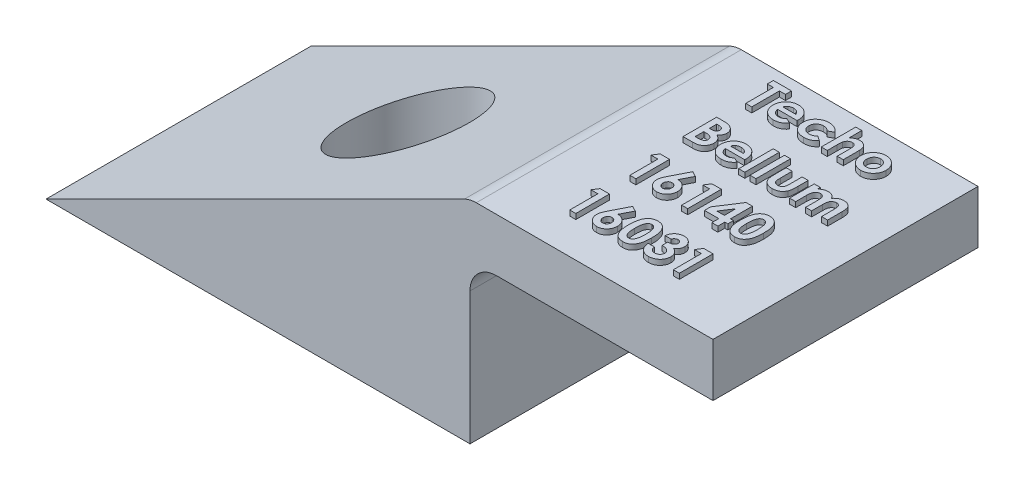
SolidWorks part; units mm, degrees
ref_plane "Front" through (0, 0, 0) normal (0, 0, 1) x (1, 0, 0)
ref_plane "Top" through (0, 0, 0) normal (0, 1, 0) x (1, 0, 0)
ref_plane "Right" through (0, 0, 0) normal (1, 0, 0) x (0, 0, -1)
sketch "Sketch1" plane through (0, 0, 0) normal (0, 0, 1) x (1, 0, 0)
  line L0 (-80, 0) -> (0, 40)
  line L1 (-80, 0) -> (0, 0)
  line L4 (0, 0) -> (0, 29.991)
  line L5 (0, 40) -> (45.845, 40)
  line L6 (45.845, 40) -> (45.845, 29.991)
  line L7 (45.845, 29.991) -> (0, 29.991)
  point P0 (0, 0)
extrude "Boss-Extrude1" add sketch "Sketch1" along normal blind 50
sketch "Sketch3" plane through (0, 40, 0) normal (0, 1, 0) x (1, 0, 0)
  text T0 "<b>Techo</b>\r\n<b>Bellum</b>\r\n<b>16140</b>\r\n<b>16031</b>\r\n"
extrude "Boss-Extrude3" add sketch "Sketch3" along normal blind 1
fillet "Fillet2" radius 5 2 edges at (0, 29.991, 25) (0, 40, 25)
sketch "Sketch5" plane through (0, 40, 0) normal (0, 1, 0) x (1, 0, 0)
  circle A0 centre (-36.7258, -25) radius 11.6115
extrude "Cut-Extrude1" cut sketch "Sketch5" against normal blind 62
